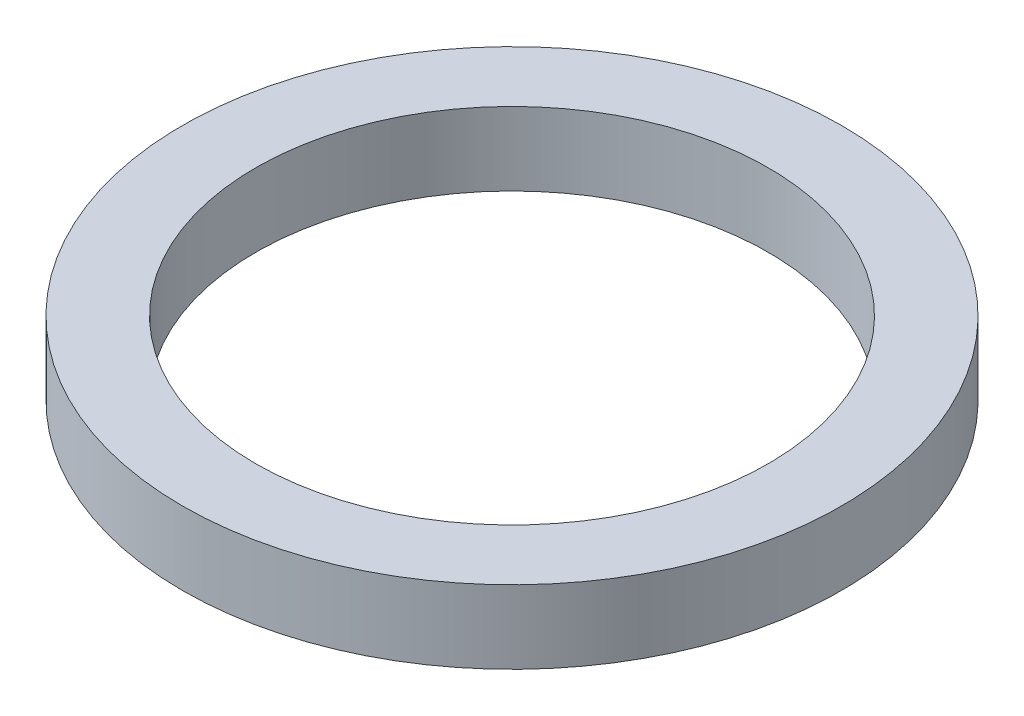
SolidWorks part; units mm, degrees
ref_plane "前视基准面" through (0, 0, 0) normal (0, 0, 1) x (1, 0, 0)
ref_plane "上视基准面" through (0, 0, 0) normal (0, 1, 0) x (1, 0, 0)
ref_plane "右视基准面" through (0, 0, 0) normal (1, 0, 0) x (0, 0, -1)
sketch "草图1" plane through (0, 0, 0) normal (0, 1, 0) x (1, 0, 0)
  circle A0 centre (0, 0) radius 35
  circle A1 centre (0, 0) radius 45
extrude "凸台-拉伸1" add sketch "草图1" along normal blind 10
